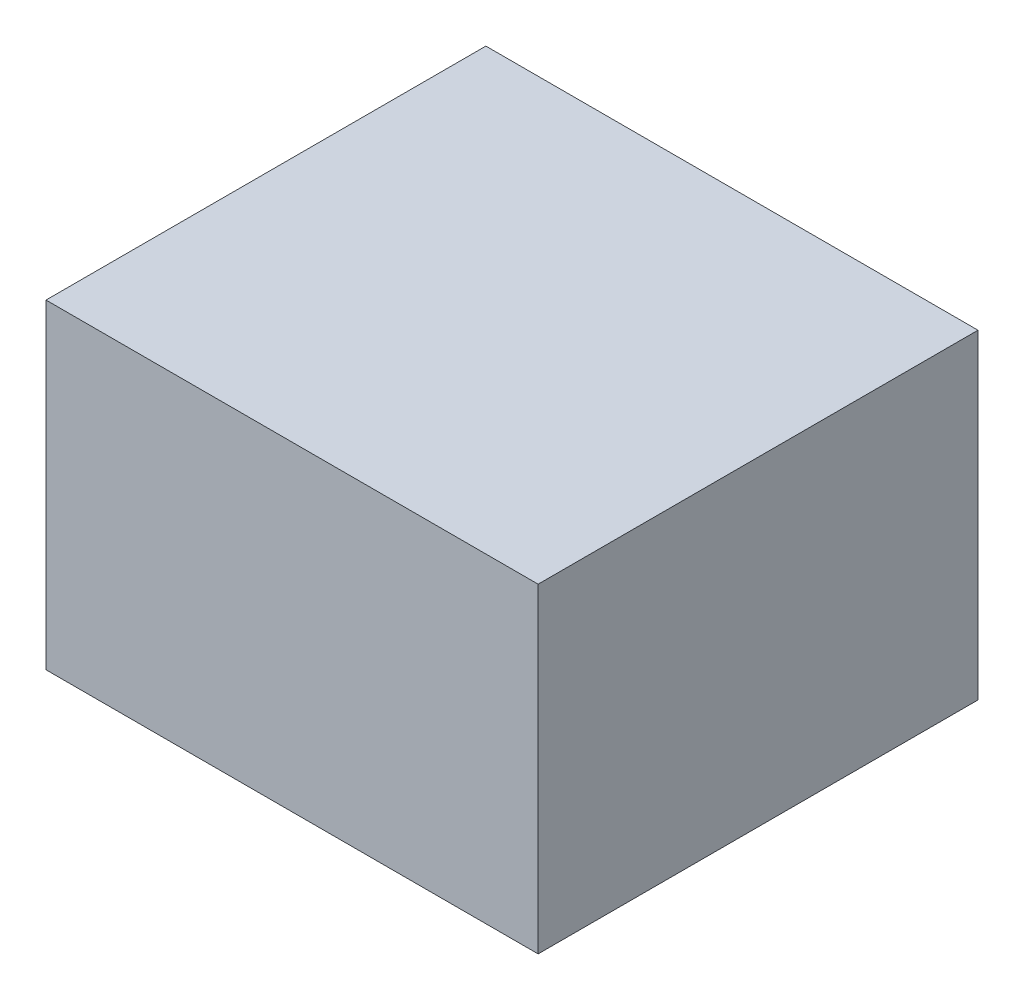
SolidWorks part; units mm, degrees
ref_plane "Front Plane" through (0, 0, 0) normal (0, 0, 1) x (1, 0, 0)
ref_plane "Top Plane" through (0, 0, 0) normal (0, 1, 0) x (1, 0, 0)
ref_plane "Right Plane" through (0, 0, 0) normal (1, 0, 0) x (0, 0, -1)
sketch "Sketch1" plane through (0, 0, 0) normal (0, 1, 0) x (1, 0, 0)
  line L1 (-146, -130.5) -> (146, -130.5)
  line L2 (-146, -130.5) -> (-146, 130.5)
  line L3 (-146, 130.5) -> (146, 130.5)
  line L4 (146, -130.5) -> (146, 130.5)
  line L5 (-146, -130.5) -> (146, 130.5) construction
  line L6 (-146, 130.5) -> (146, -130.5) construction
  point P0 (0, 0)
  dimension "D1" = 292
  dimension "D2" = 261
extrude "Boss-Extrude1" add sketch "Sketch1" along normal mid plane 190
ref_plane "Plane4" through (0, 0, 69.5) normal (0, 0, 1) x (1, 0, 0)
